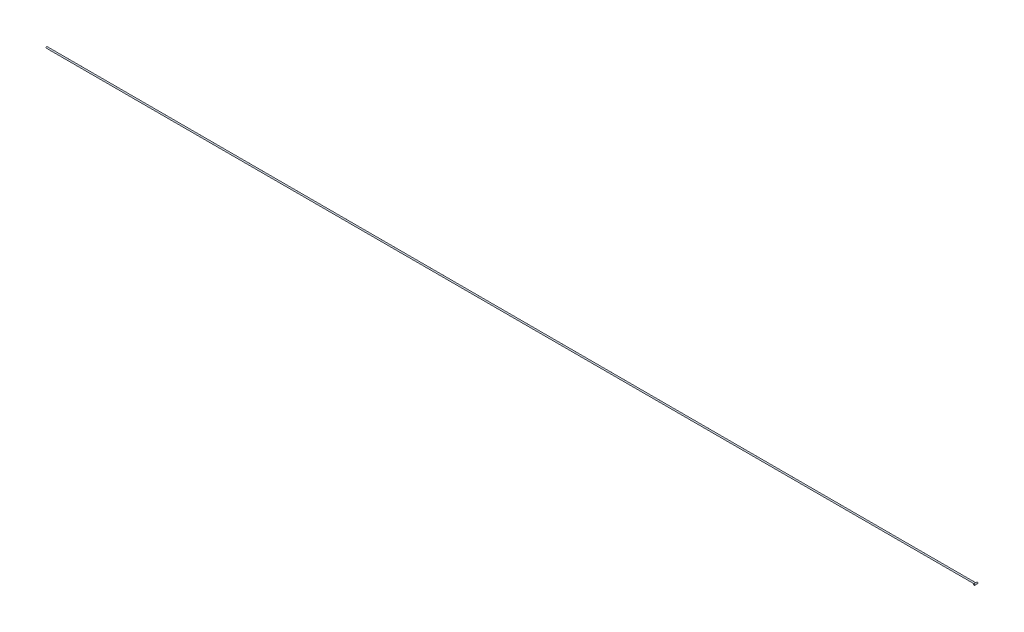
SolidWorks part; units mm, degrees
ref_plane "Plan de face" through (0, 0, 0) normal (0, 0, 1) x (1, 0, 0)
ref_plane "Plan de dessus" through (0, 0, 0) normal (0, 1, 0) x (1, 0, 0)
ref_plane "Plan de droite" through (0, 0, 0) normal (1, 0, 0) x (0, 0, -1)
sketch "Esquisse1" plane through (0, 0, 0) normal (0, 0, 1) x (1, 0, 0)
  line L0 (-716, 0) -> (716, 0)
  dimension "D1" = 1432
sweep "Balayage1" add path "Esquisse1" circular profile diameter 2 parameters "D3"=2
sketch "Esquisse16" plane through (716, 0, 0) normal (1, 0, 0) x (0, 0, -1)
  line L0 (-2.5, 0) -> (2.5, 0)
  dimension "D1" = 5
sweep "Balayage2" add path "Esquisse16" circular profile diameter 2 parameters "D3"=2
